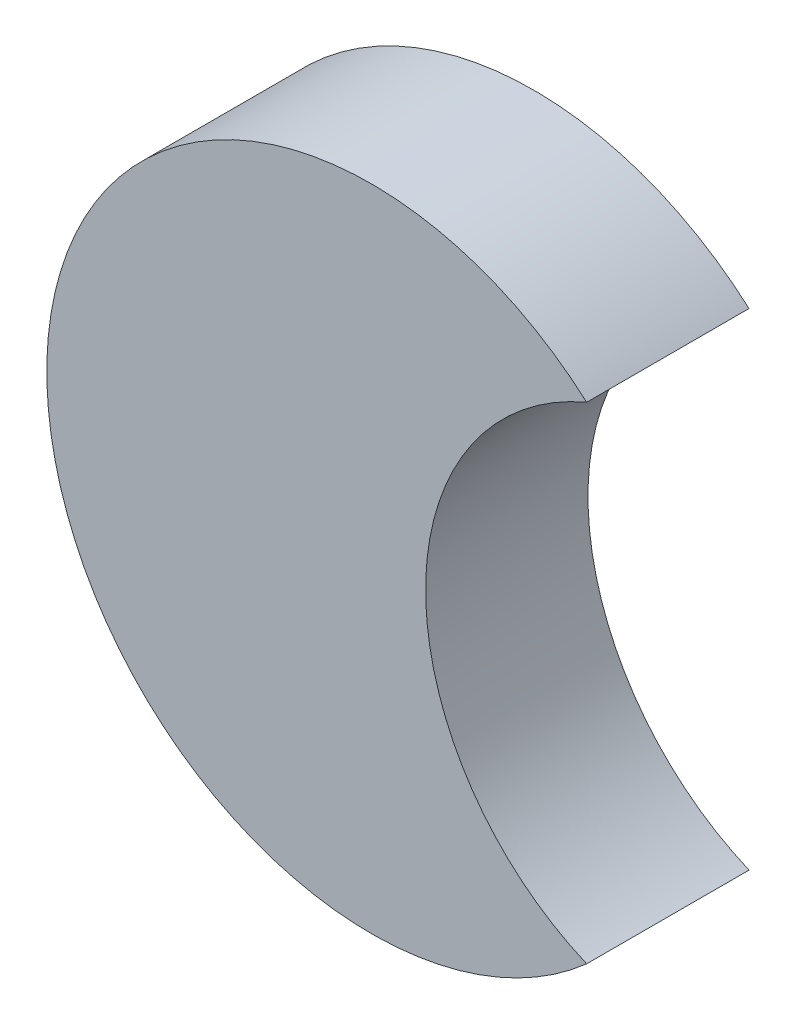
SolidWorks part; units mm, degrees
ref_plane "Front Plane" through (0, 0, 0) normal (0, 0, 1) x (1, 0, 0)
ref_plane "Top Plane" through (0, 0, 0) normal (0, 1, 0) x (1, 0, 0)
ref_plane "Right Plane" through (0, 0, 0) normal (1, 0, 0) x (0, 0, -1)
sketch "Sketch1" plane through (0, 0, 0) normal (0, 0, 1) x (1, 0, 0)
  circle A0 centre (0, 0) radius 60
extrude "Boss-Extrude1" add sketch "Sketch1" along normal blind 30
sketch "Sketch2" plane through (0, 0, 30) normal (0, 0, 1) x (1, 0, 0)
  circle A0 centre (58.8, 0) radius 48.8
extrude "Cut-Extrude1" cut sketch "Sketch2" against normal blind 30
